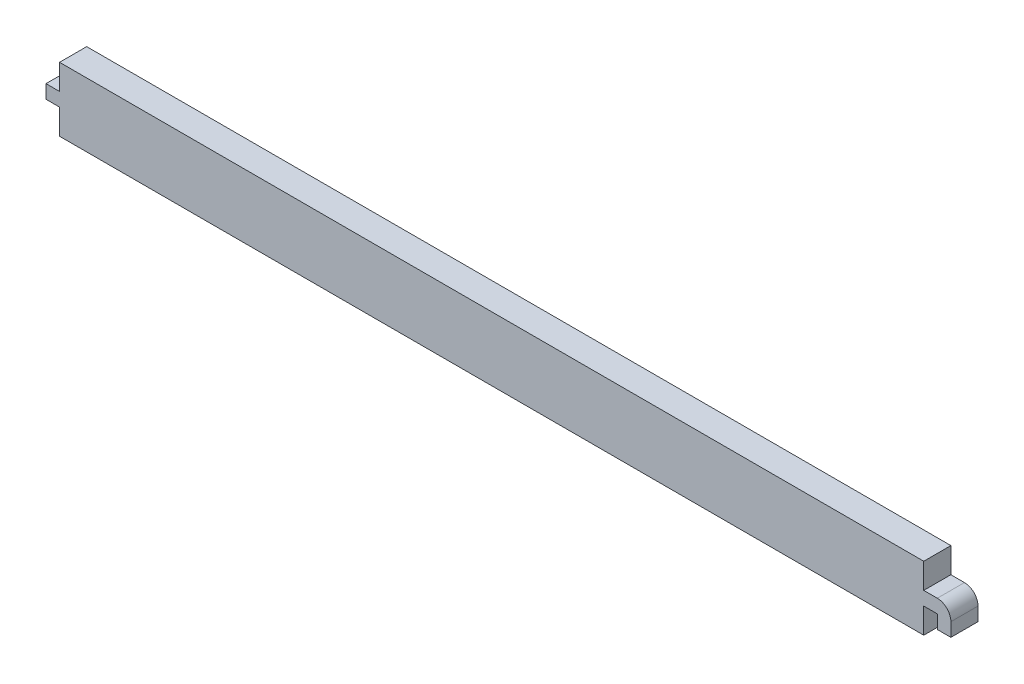
SolidWorks part; units mm, degrees
material "6061 Alloy"
ref_plane "Front Plane" through (0, 0, 0) normal (0, 0, 1) x (1, 0, 0)
ref_plane "Top Plane" through (0, 0, 0) normal (0, 1, 0) x (1, 0, 0)
ref_plane "Right Plane" through (0, 0, 0) normal (1, 0, 0) x (0, 0, -1)
sketch "Sketch1" plane through (0, 0, 0) normal (0, 0, 1) x (1, 0, 0)
  line L1 (0, 0) -> (202.3, 0)
  line L2 (0, 0) -> (0, 15)
  line L3 (0, 15) -> (202.3, 15)
  line L4 (202.3, 0) -> (202.3, 15)
  dimension "D1" = 202.3
  dimension "D2" = 15
extrude "Boss-Extrude1" add sketch "Sketch1" along normal blind 6.35 contours L3 L4 L1 L2
sketch "Sketch2" plane through (0, 0, 6.35) normal (0, 0, 1) x (1, 0, 0)
  line L1 (208.65, 5.9125) -> (208.65, 2.7375)
  line L2 (208.65, 2.7375) -> (205.475, 2.7375)
  line L3 (0, 7.5) -> (0, 9.0875)
  line L4 (0, 0) -> (0, 15) construction
  line L5 (0, 9.0875) -> (-3.175, 9.0875)
  line L6 (-3.175, 9.0875) -> (-3.175, 5.9125)
  line L7 (-3.175, 5.9125) -> (0, 5.9125)
  line L8 (0, 5.9125) -> (0, 7.5)
  line L9 (202.3, 5.9125) -> (202.3, 7.5)
  line L13 (202.3, 7.5) -> (202.3, 9.0875)
  line L15 (205.475, 2.7375) -> (205.475, 5.9125)
  line L16 (205.475, 5.9125) -> (202.3, 5.9125)
  line L17 (205.475, 9.0875) -> (202.3, 9.0875)
  arc A0 (205.475, 9.0875) -> (208.65, 5.9125) centre (205.475, 5.9125) cw
extrude "Boss-Extrude2" add sketch "Sketch2" against normal up to surface (6.35 mm away) contours L5 L6 L7 L8 L3 | L17 L13 L9 L16 L15 L2 L1 A0 up to face at (101.15, 7.5, 0)
sketch "Sketch3" plane through (0, 0, 6.35) normal (0, 0, 1) x (1, 0, 0)
  line L12 (0, 5.9125) -> (0, 0)
  line L13 (0, 0) -> (202.3, 0)
  line L14 (202.3, 0) -> (202.3, 5.9125)
  line L15 (202.3, 5.9125) -> (205.475, 5.9125)
  line L16 (202.3, 5.9125) -> (205.475, 5.9125)
  line L17 (205.475, 9.0875) -> (202.3, 9.0875)
  line L18 (202.3, 9.0875) -> (202.3, 15)
  line L19 (202.3, 15) -> (0, 15)
  line L20 (0, 15) -> (0, 9.0875)
  line L21 (0, 9.0875) -> (-3.175, 9.0875)
  line L22 (-3.175, 9.0875) -> (-3.175, 5.9125)
  line L23 (-3.175, 5.9125) -> (0, 5.9125)
  line L24 (0, 5.9125) -> (0, 0)
  line L25 (0, 0) -> (202.3, 0)
  line L26 (202.3, 0) -> (202.3, 5.9125)
  line L29 (205.475, 9.0875) -> (202.3, 9.0875)
  line L30 (202.3, 9.0875) -> (202.3, 15)
  line L31 (202.3, 15) -> (0, 15)
  line L32 (0, 15) -> (0, 9.0875)
  line L33 (0, 9.0875) -> (-3.175, 9.0875)
  line L34 (-3.175, 9.0875) -> (-3.175, 5.9125)
  line L35 (-3.175, 5.9125) -> (0, 5.9125)
  line L38 (205.475, 5.9125) -> (205.475, 2.7375)
  line L39 (205.475, 5.9125) -> (205.475, 2.7375)
  line L40 (205.475, 2.7375) -> (208.65, 2.7375)
  line L41 (205.475, 2.7375) -> (208.65, 2.7375)
  line L42 (208.65, 2.7375) -> (208.65, 5.9125)
  line L43 (208.65, 2.7375) -> (208.65, 5.9125)
  arc A1 (208.65, 5.9125) -> (205.475, 9.0875) centre (205.475, 5.9125) ccw
  arc A2 (208.65, 5.9125) -> (205.475, 9.0875) centre (205.475, 5.9125) ccw
  dimension "D1" = 0
